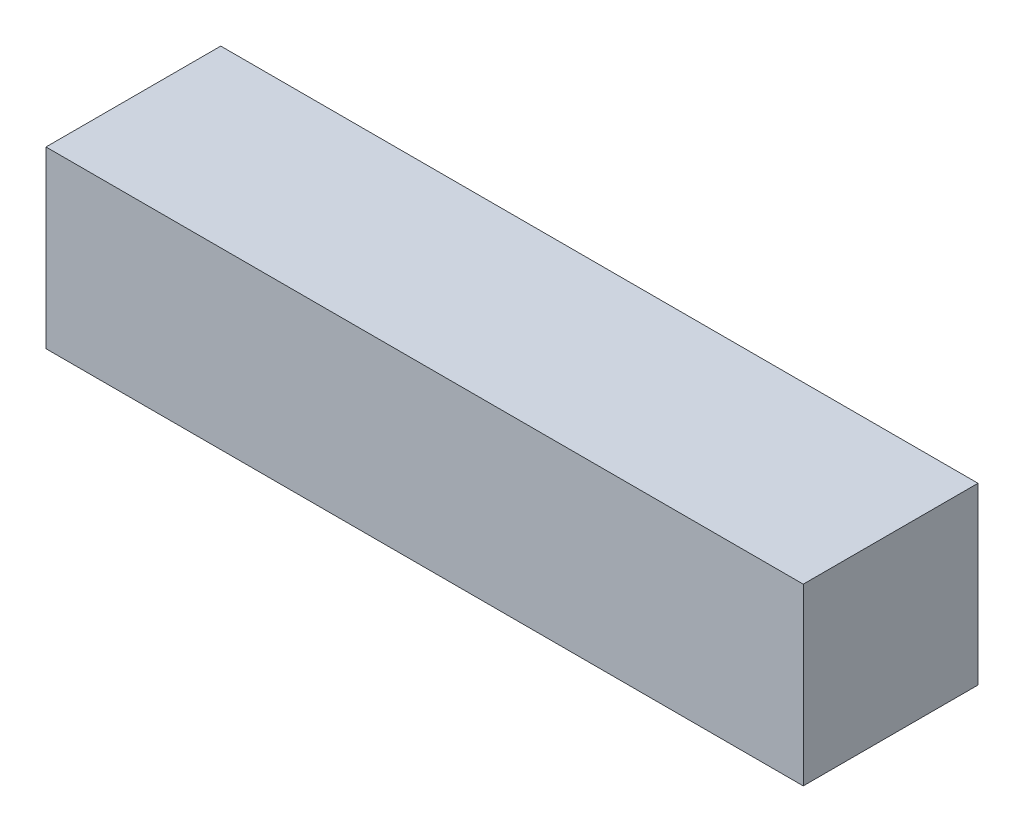
SolidWorks part; units mm, degrees
material "Pine"
ref_plane "Front Plane" through (0, 0, 0) normal (0, 0, 1) x (1, 0, 0)
ref_plane "Top Plane" through (0, 0, 0) normal (0, 1, 0) x (1, 0, 0)
ref_plane "Right Plane" through (0, 0, 0) normal (1, 0, 0) x (0, 0, -1)
sketch "Sketch1" plane through (0, 0, 0) normal (0, 0, 1) x (1, 0, 0)
  line L1 (-82.55, 19.05) -> (82.55, 19.05)
  line L2 (-82.55, 19.05) -> (-82.55, -19.05)
  line L3 (-82.55, -19.05) -> (82.55, -19.05)
  line L4 (82.55, 19.05) -> (82.55, -19.05)
  point P4 (0, 19.05)
  point P6 (82.55, 0)
  dimension "D1" = 165.1
  dimension "D2" = 38.1
extrude "Boss-Extrude1" add sketch "Sketch1" along normal blind 38.1
